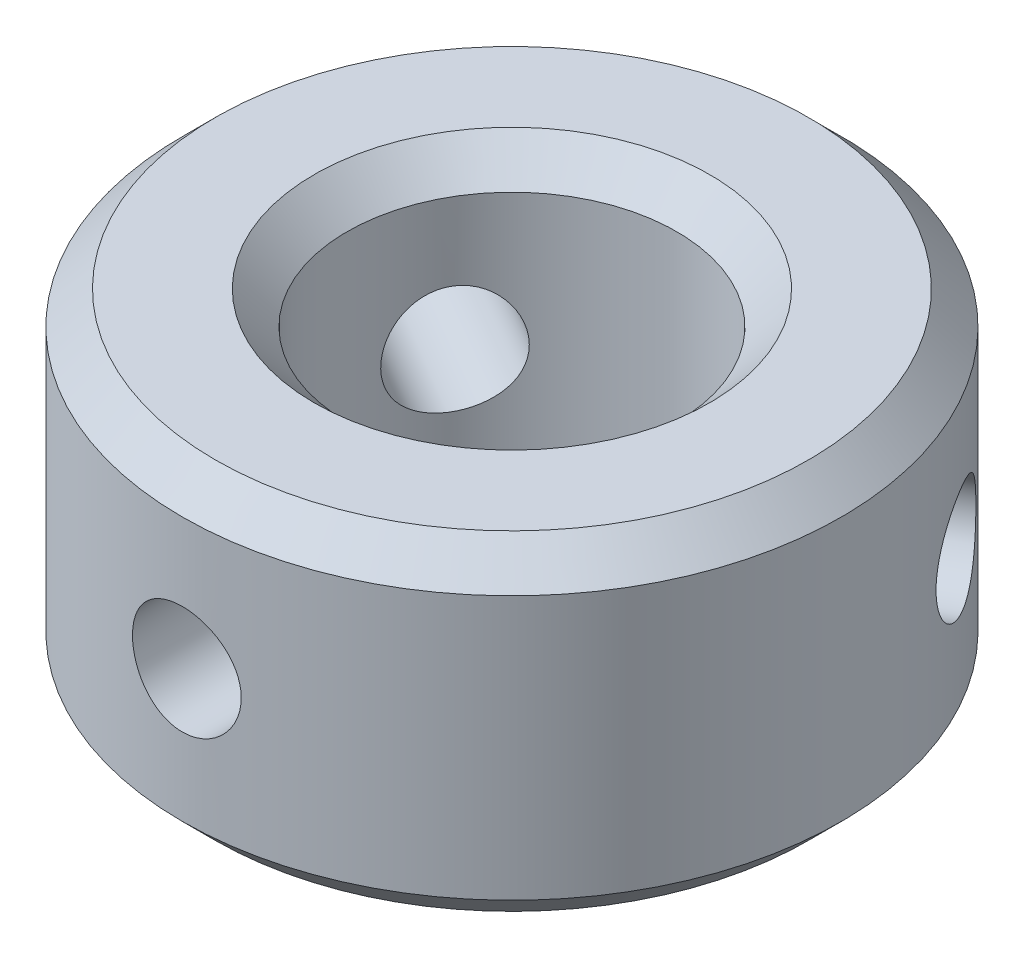
SolidWorks part; units mm, degrees
material "Plain Carbon Steel"
ref_plane "Front Plane" through (0, 0, 0) normal (0, 0, 1) x (1, 0, 0)
ref_plane "Top Plane" through (0, 0, 0) normal (0, 1, 0) x (1, 0, 0)
ref_plane "Right Plane" through (0, 0, 0) normal (1, 0, 0) x (0, 0, -1)
sketch "Sketch1" plane through (0, 0, 0) normal (0, 1, 0) x (1, 0, 0)
  circle A0 centre (0, 0) radius 10
  circle A1 centre (0, 0) radius 5
  dimension "D1" = 10
  dimension "D2" = 20
extrude "Boss-Extrude1" add sketch "Sketch1" against normal blind 10
chamfer "Chamfer1" distance 1 angle 45 4 edges at (0, -10, 5) (0, 0, 5) (0, -10, 10) (0, 0, 10)
hole_wizard "M4 Tapped Hole1" positions "Sketch5" profile "Sketch3" tap size "M4" standard "ISO"
sketch "Sketch5" plane through (0, 0, 0) normal (0, 0, 1) x (1, 0, 0)
  line L0 (0, 0) -> (0, -10) construction
  line L1 (-9, -10) -> (9, -10) construction
  point P0 (0, -5)
  point P20 (0, -5)
sketch "Sketch3" plane through (0, -5, 0) normal (1, 0, 0) x (0, 1, 0)
  line L0 (0, 0) -> (0, 10)
  line L1 (0, 10) -> (1.65, 10)
  line L2 (1.65, 10) -> (1.65, 0)
  line L5 (1.65, 0) -> (0, 0)
  line L11 (0, -6.35) -> (0, 107.95) construction
  dimension "Thru Tap Drill Dia." = 3.3
  dimension "Thru Tap Drill Depth" = 10
cosmetic thread "Hole Thread1"
pattern_circular "CirPattern1" count 3 over 360 about axis through (0, -1, 0) along (0, 1, 0) of "M4 Tapped Hole1"
cosmetic thread "Hole Thread2"
cosmetic thread "Hole Thread3"
